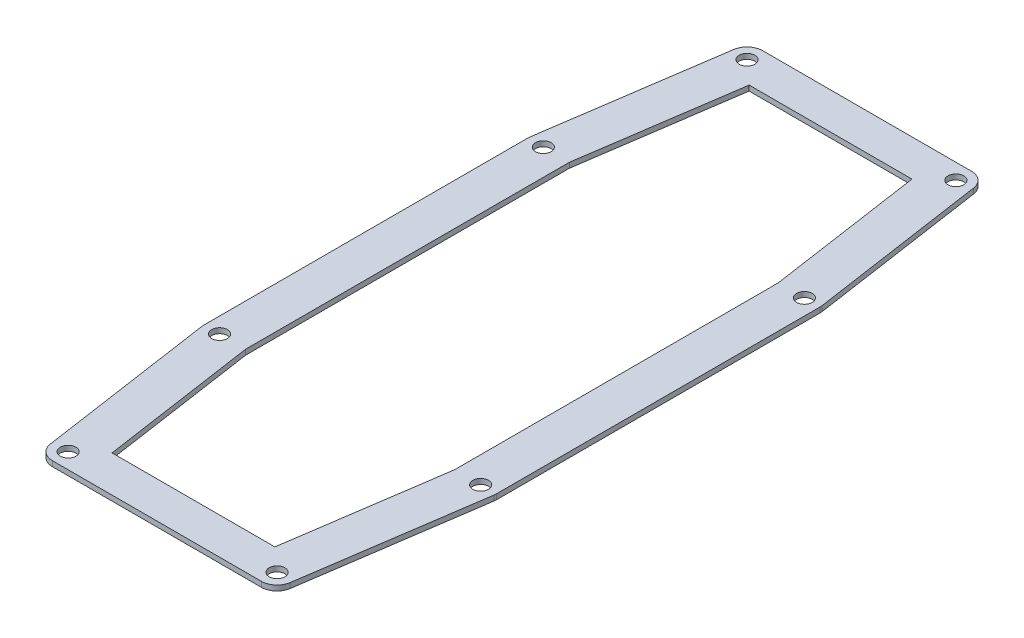
SolidWorks part; units mm, degrees
ref_plane "前视基准面" through (0, 0, 0) normal (0, 0, 1) x (1, 0, 0)
ref_plane "上视基准面" through (0, 0, 0) normal (0, 1, 0) x (1, 0, 0)
ref_plane "右视基准面" through (0, 0, 0) normal (1, 0, 0) x (0, 0, -1)
sketch "草图1" plane through (0, 0, 0) normal (0, 1, 0) x (1, 0, 0)
  line L0 (5, 99) -> (45, 99)
  line L1 (0, 0) -> (50, 0) construction
  line L2 (0, 0) -> (0, 62) construction
  line L3 (0, 62) -> (50, 62) construction
  line L4 (50, 0) -> (50, 62) construction
  line L5 (5, 96) -> (45, 96) construction
  line L6 (5, 96) -> (5, -34) construction
  line L7 (5, -34) -> (45, -34) construction
  line L8 (45, 96) -> (45, -34) construction
  line L9 (2.0319, 96.4365) -> (-2.9681, 62.4365)
  line L10 (-3, 62) -> (-3, 0)
  line L11 (-2.9681, -0.4365) -> (2.0319, -34.4365)
  line L12 (5, -37) -> (45, -37)
  line L13 (25, 62) -> (25, 0) construction
  line L14 (52.9681, -0.4365) -> (47.9681, -34.4365)
  line L15 (53, 62) -> (53, 0)
  line L16 (47.9681, 96.4365) -> (52.9681, 62.4365)
  line L17 (9.4118, 92) -> (5, 62)
  line L18 (5, 62) -> (5, 0)
  line L19 (5, 0) -> (9.4118, -30)
  line L20 (9.4118, -30) -> (40.5882, -30)
  line L21 (9.4118, 92) -> (40.5882, 92)
  line L22 (45, 0) -> (40.5882, -30)
  line L23 (45, 62) -> (45, 0)
  line L24 (40.5882, 92) -> (45, 62)
  circle A0 centre (0, 62) radius 1.5
  circle A1 centre (50, 62) radius 1.5
  circle A2 centre (0, 0) radius 1.5
  circle A3 centre (50, 0) radius 1.5
  circle A4 centre (5, 96) radius 1.5
  circle A5 centre (45, 96) radius 1.5
  circle A6 centre (5, -34) radius 1.5
  circle A7 centre (45, -34) radius 1.5
  arc A8 (5, 99) -> (2.0319, 96.4365) centre (5, 96) ccw
  arc A9 (2.0319, -34.4365) -> (5, -37) centre (5, -34) ccw
  arc A10 (-3, 0) -> (-2.9681, -0.4365) centre (0, 0) ccw
  arc A11 (-2.9681, 62.4365) -> (-3, 62) centre (0, 62) ccw
  arc A12 (47.9681, -34.4365) -> (45, -37) centre (45, -34) cw
  arc A13 (53, 0) -> (52.9681, -0.4365) centre (50, 0) cw
  arc A14 (52.9681, 62.4365) -> (53, 62) centre (50, 62) cw
  arc A15 (45, 99) -> (47.9681, 96.4365) centre (45, 96) cw
  point P42 (38.759, 92.0665)
  point P45 (37.6657, 90.9784)
  point P46 (10.6366, 91.8793)
  point P47 (39.6995, 91.8793)
  point P48 (9.6338, -28.3961)
  point P49 (40.3662, -28.6981)
  dimension "D3" = 3
  dimension "D8" = 3
  dimension "D9" = 3
  dimension "D10" = 3
  dimension "D11" = 3
  dimension "D1" = 50
  dimension "D2" = 62
  dimension "D4" = 5
  dimension "D5" = 7
  dimension "D6" = 34
  dimension "D7" = 34
  dimension "D12" = 7
extrude "凸台-拉伸1" add sketch "草图1" along normal blind 1
